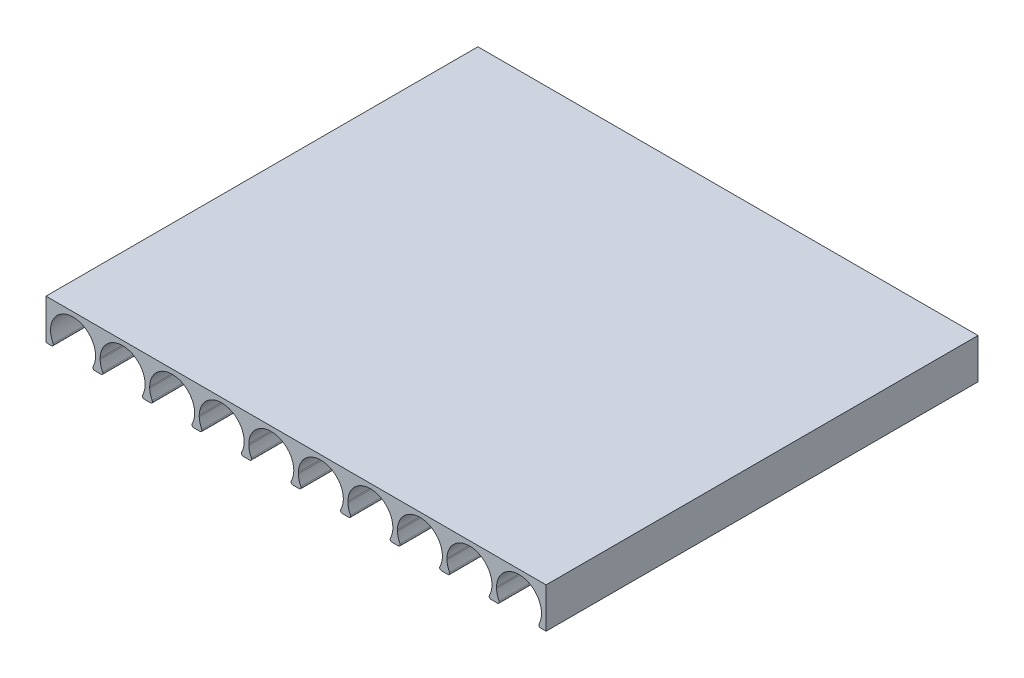
SolidWorks part; units mm, degrees
ref_plane "Front Plane" through (0, 0, 0) normal (0, 0, 1) x (1, 0, 0)
ref_plane "Top Plane" through (0, 0, 0) normal (0, 1, 0) x (1, 0, 0)
ref_plane "Right Plane" through (0, 0, 0) normal (1, 0, 0) x (0, 0, -1)
sketch "Sketch1" plane through (0, 0, 0) normal (0, 0, 1) x (1, 0, 0)
  line L0 (0, 0) -> (1.22, 0)
  line L1 (0.635, 1.8204) -> (6.885, 1.8204) construction
  line L2 (0, 0) -> (0, 5.5804)
  line L3 (0, 5.5804) -> (7.52, 5.5804)
  line L4 (0, 5.5804) -> (3.76, 1.8204) construction
  line L5 (6.3, 0) -> (7.52, 0)
  line L6 (7.52, 0) -> (7.52, 5.5804)
  line L7 (3.76, 1.8204) -> (7.52, 5.5804) construction
  arc A0 (1.22, 0) -> (6.3, 0) centre (3.76, 1.8204) cw
  dimension "D1" = 6.25
  dimension "D2" = 5.08
  dimension "D3" = 0.635
extrude "Boss-Extrude1" add sketch "Sketch1" along normal mid plane 60
fillet "Fillet1" radius 0.254 2 edges at (1.22, 0, 0) (6.3, 0, 0)
sketch "Sketch2" plane through (0, 0, 30) normal (0, 0, 1) x (1, 0, 0)
  circle A0 centre (3.76, 1.5263) radius 3
  point P5 (3.8447, 2.5285)
  dimension "D1" = 6
pattern_linear "LPattern1" count 10 spacing 6.8834 along (-1, 0, 0) of "Boss-Extrude1", "Fillet1"
